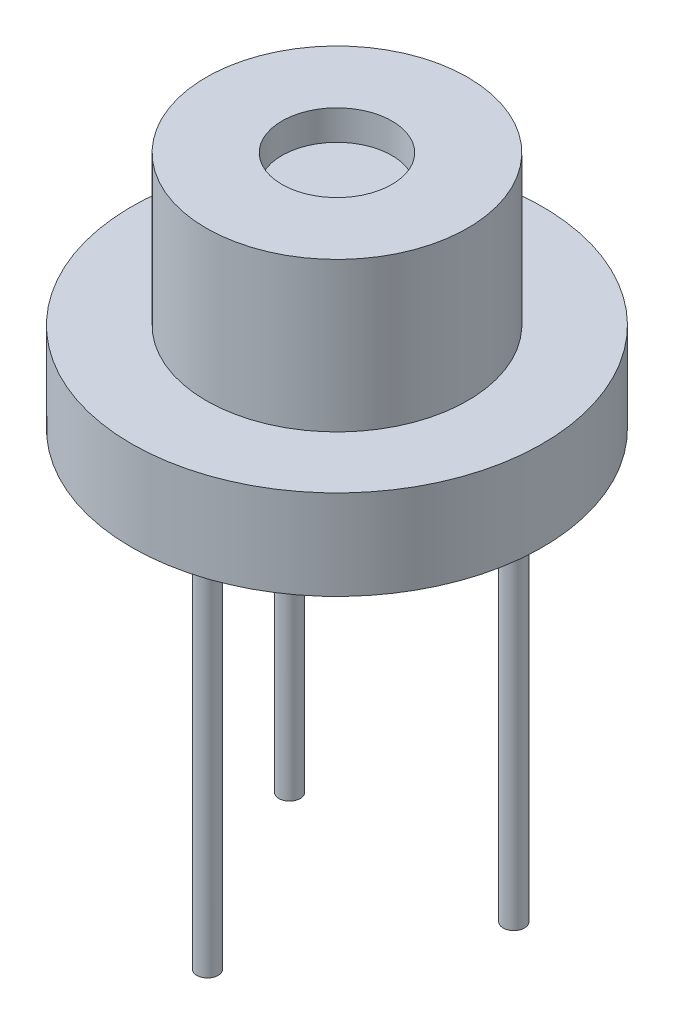
SolidWorks part; units mm, degrees
ref_plane "Front Plane" through (0, 0, 0) normal (0, 0, 1) x (1, 0, 0)
ref_plane "Top Plane" through (0, 0, 0) normal (0, 1, 0) x (1, 0, 0)
ref_plane "Right Plane" through (0, 0, 0) normal (1, 0, 0) x (0, 0, -1)
sketch "Sketch1" plane through (0, 0, 0) normal (0, 1, 0) x (1, 0, 0)
  circle A0 centre (0, 0) radius 2.75
  dimension "D1" = 5.5
extrude "Boss-Extrude1" add sketch "Sketch1" along normal blind 1.2
sketch "Sketch2" plane through (0, 1.2, 0) normal (0, 1, 0) x (1, 0, 0)
  circle A0 centre (0, 0) radius 1.75
  dimension "D1" = 3.5
extrude "Boss-Extrude2" add sketch "Sketch2" along normal blind 2
sketch "Sketch3" plane through (0, 3.2, 0) normal (0, 1, 0) x (1, 0, 0)
  circle A0 centre (0, 0) radius 0.7363
extrude "Cut-Extrude1" cut sketch "Sketch3" against normal blind 0.4
sketch "Sketch4" plane through (0, 0, 0) normal (0, -1, 0) x (1, 0, 0)
  circle A0 centre (0, 1.7333) radius 0.1431
  circle A1 centre (1.5011, -0.8666) radius 0.1431
  circle A2 centre (-1.5011, -0.8666) radius 0.1431
  point P8 (0, 0)
  dimension "D1" = 3
extrude "Boss-Extrude3" add sketch "Sketch4" along normal blind 5.4
